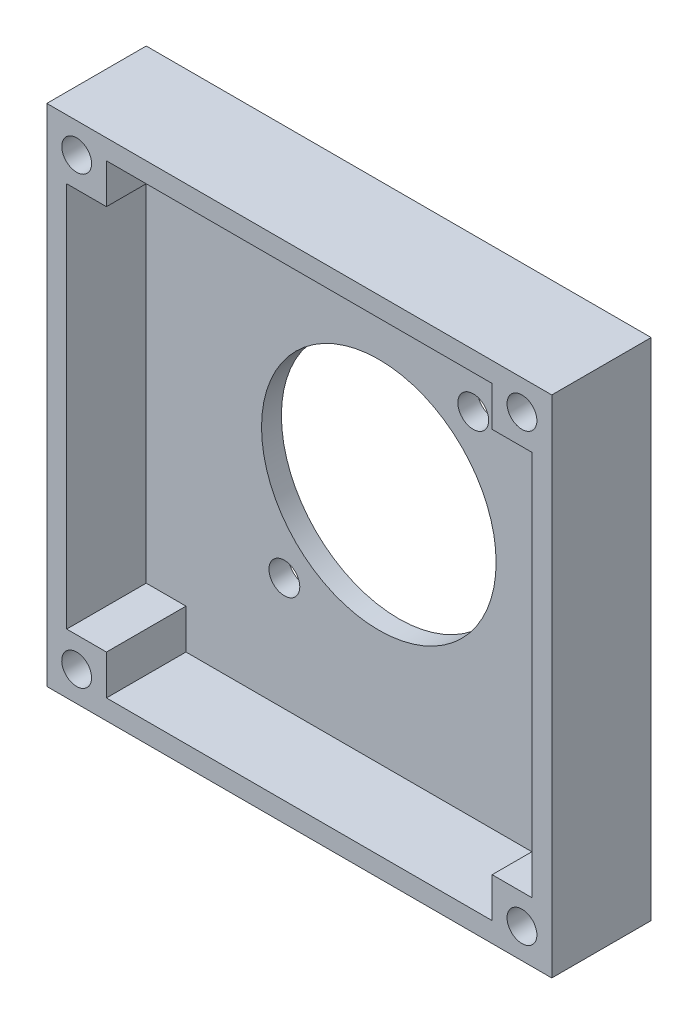
SolidWorks part; units mm, degrees
ref_plane "Front Plane" through (0, 0, 0) normal (0, 0, 1) x (1, 0, 0)
ref_plane "Top Plane" through (0, 0, 0) normal (0, 1, 0) x (1, 0, 0)
ref_plane "Right Plane" through (0, 0, 0) normal (1, 0, 0) x (0, 0, -1)
sketch "Sketch1" plane through (0, 0, 0) normal (0, 0, 1) x (1, 0, 0)
  line L0 (-25.4, -19.4) -> (-19.4, -25.4) construction
  line L1 (-23.4, -23.4) -> (23.4, -23.4)
  line L2 (-23.4, -23.4) -> (-23.4, 23.4)
  line L3 (-23.4, 23.4) -> (23.4, 23.4)
  line L4 (23.4, -23.4) -> (23.4, 23.4)
  line L5 (-25.4, -25.4) -> (25.4, -25.4)
  line L6 (-25.4, -25.4) -> (-25.4, 25.4)
  line L7 (-25.4, 25.4) -> (25.4, 25.4)
  line L8 (25.4, -25.4) -> (25.4, 25.4)
  line L9 (-25.4, -25.4) -> (25.4, 25.4) construction
  line L10 (-25.4, 25.4) -> (25.4, -25.4) construction
  line L11 (-25.4, -25.4) -> (-19.4, -25.4)
  line L12 (-25.4, -25.4) -> (-25.4, -19.4)
  line L13 (-25.4, -19.4) -> (-19.4, -19.4)
  line L14 (-19.4, -25.4) -> (-19.4, -19.4)
  line L15 (0, 25.4) -> (0, -25.4) construction
  line L16 (-25.4, 0) -> (25.4, 0) construction
  line L17 (25.4, -19.4) -> (19.4, -19.4)
  line L18 (19.4, -25.4) -> (19.4, -19.4)
  line L19 (25.4, -25.4) -> (19.4, -25.4)
  line L20 (25.4, -25.4) -> (25.4, -19.4)
  line L21 (25.4, 25.4) -> (19.4, 25.4)
  line L22 (19.4, 25.4) -> (19.4, 19.4)
  line L23 (25.4, 19.4) -> (19.4, 19.4)
  line L24 (25.4, 25.4) -> (25.4, 19.4)
  line L25 (-25.4, 19.4) -> (-19.4, 19.4)
  line L26 (-19.4, 25.4) -> (-19.4, 19.4)
  line L27 (-25.4, 25.4) -> (-19.4, 25.4)
  line L28 (-25.4, 25.4) -> (-25.4, 19.4)
  line L29 (-25.4, 19.4) -> (-19.4, 25.4) construction
  line L30 (25.4, -19.4) -> (19.4, -19.4)
  line L31 (19.4, -25.4) -> (19.4, -19.4)
  line L32 (25.4, -25.4) -> (19.4, -25.4)
  line L33 (25.4, -25.4) -> (25.4, -19.4)
  line L34 (25.4, 25.4) -> (19.4, 25.4)
  line L35 (19.4, 25.4) -> (19.4, 19.4)
  line L36 (25.4, 19.4) -> (19.4, 19.4)
  line L37 (25.4, 25.4) -> (25.4, 19.4)
  circle A4 centre (-22.4, 22.4) radius 1.5
  circle A5 centre (-22.4, -22.4) radius 1.5
  circle A6 centre (22.4, -22.4) radius 1.5
  circle A7 centre (22.4, 22.4) radius 1.5
  point P5 (0, 0)
  dimension "D8" = 3
  dimension "D9" = 3
  dimension "D1" = 50.8
  dimension "D2" = 50.8
  dimension "D3" = 2
  dimension "D4" = 2
  dimension "D5" = 2
  dimension "D6" = 2
  dimension "D7" = 6
sketch "Sketch3" plane through (0, 0, 0) normal (0, 0, 1) x (1, 0, 0)
  line L0 (0, 11.8) -> (0, -11.8) construction
  line L1 (-25.4, -25.4) -> (25.4, -25.4)
  line L2 (-25.4, -25.4) -> (-25.4, 25.4)
  line L3 (-25.4, 25.4) -> (25.4, 25.4)
  line L4 (25.4, -25.4) -> (25.4, 25.4)
  line L5 (-25.4, -25.4) -> (25.4, 25.4) construction
  line L6 (-25.4, 25.4) -> (25.4, -25.4) construction
  line L7 (-11.8, 0) -> (11.8, 0) construction
  circle A0 centre (0, 0) radius 11.8
  circle A1 centre (-9.5, -12) radius 1.55
  circle A2 centre (9.5, 12) radius 1.55
  point P0 (0, 0)
  dimension "D1" = 23.6
  dimension "D2" = 3.1
  dimension "D3" = 3.1
  dimension "D4" = 19
  dimension "D5" = 24
  dimension "D6" = 9.5
  dimension "D7" = 12
extrude "Boss-Extrude5" add sketch "Sketch3" along normal blind 2
extrude "Boss-Extrude6" add sketch "Sketch1" along normal blind 10
sketch "Sketch7" plane through (0, 0, 2) normal (0, 0, 1) x (1, 0, 0)
  line L0 (0, 25.3712) -> (0, -25.5004) construction
  line L1 (-26.3179, -0.0646) -> (25.602, -0.0646) construction
  circle A2 centre (-22.4, 22.4) radius 1.5
  circle A3 centre (22.4, 22.4) radius 1.5
  circle A4 centre (22.4, -22.5293) radius 1.5
  circle A5 centre (-22.4, -22.5293) radius 1.5
extrude "Cut-Extrude2" cut sketch "Sketch7" against normal through all
equation "\"D6@Sketch3\"=\"D4@Sketch3\"/2"
equation "\"D7@Sketch3\"=\"D5@Sketch3\"/2"
